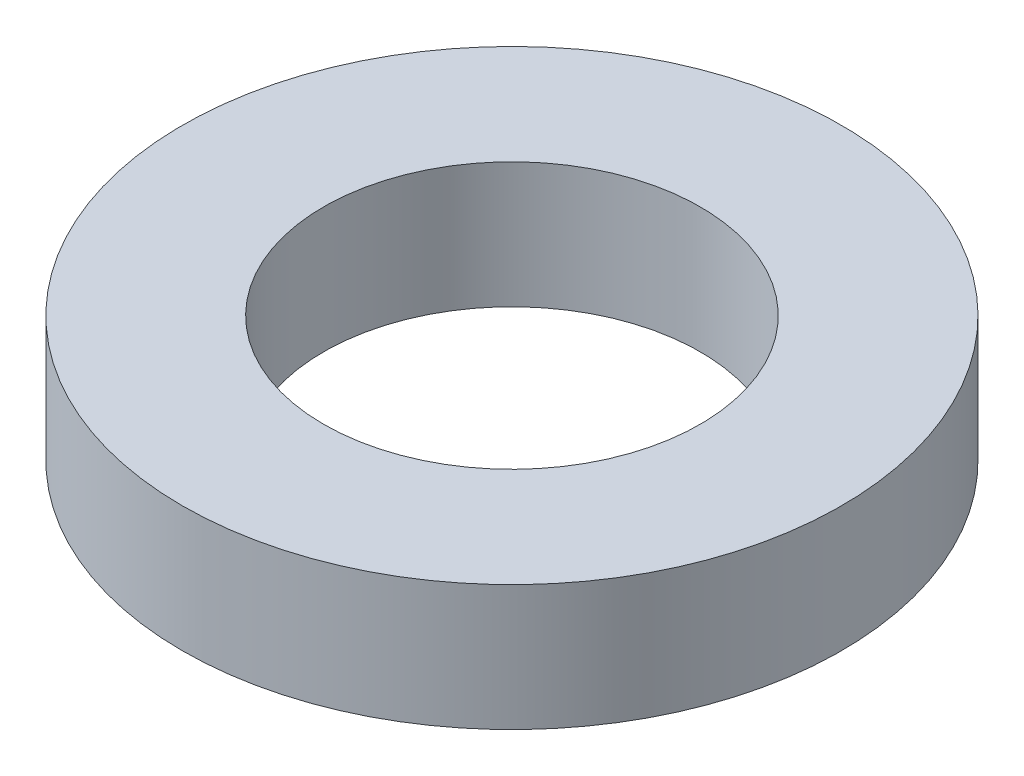
SolidWorks part; units mm, degrees
ref_plane "Front" through (0, 0, 0) normal (0, 0, 1) x (1, 0, 0)
ref_plane "Top" through (0, 0, 0) normal (0, 1, 0) x (1, 0, 0)
ref_plane "Right" through (0, 0, 0) normal (1, 0, 0) x (0, 0, -1)
sketch "草图1" plane through (0, 0, 0) normal (0, 1, 0) x (1, 0, 0)
  circle A0 centre (0, 0) radius 6
  circle A1 centre (0, 0) radius 10.5
  dimension "D1" = 12
  dimension "D2" = 21
extrude "凸台-拉伸1" add sketch "草图1" along normal blind 2
sketch "草图2" plane through (0, 2, 0) normal (0, 1, 0) x (1, 0, 0)
  circle A0 centre (0, 0) radius 6
  circle A1 centre (0, 0) radius 10.5
extrude "凸台-拉伸2" add sketch "草图2" along normal blind 2
